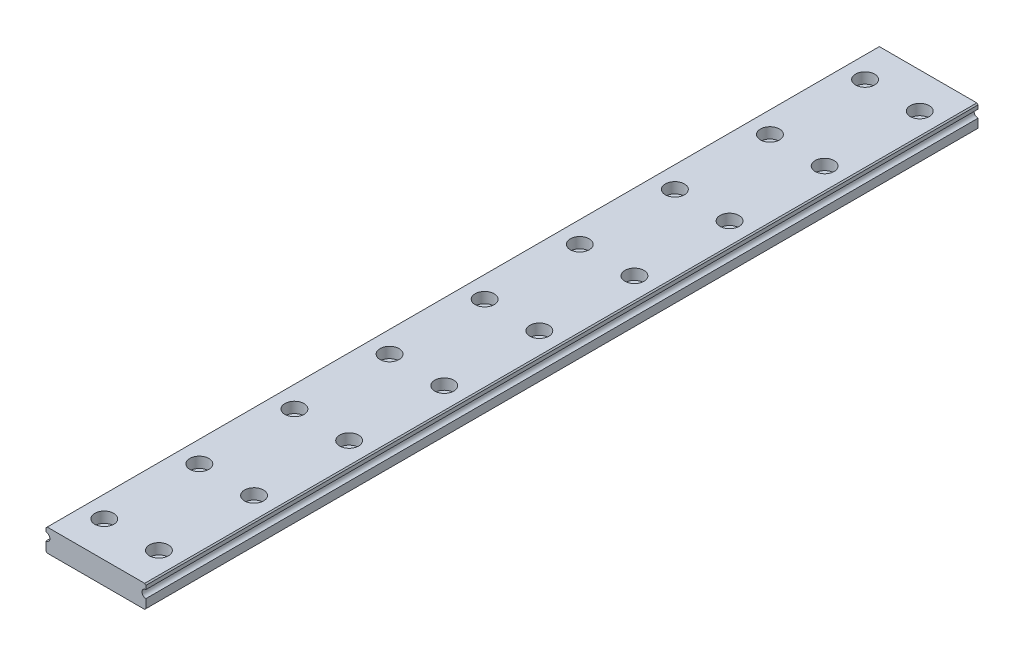
SolidWorks part; units mm, degrees
ref_plane "Front Plane" through (0, 0, 0) normal (0, 0, 1) x (1, 0, 0)
ref_plane "Top Plane" through (0, 0, 0) normal (0, 1, 0) x (1, 0, 0)
ref_plane "Right Plane" through (0, 0, 0) normal (1, 0, 0) x (0, 0, -1)
ref_plane "Plane1" through (0, 0, 0) normal (0, 0, 1) x (1, 0, 0)
sketch "Sketch1" plane through (0, 0, 0) normal (0, 0, 1) x (1, 0, 0)
  line L0 (-21, 9.005) -> (-21, 7.456)
  line L1 (-21, 4.176) -> (-21, 0.495)
  line L2 (-21, 0.495) -> (-20.505, 0)
  line L3 (-20.505, 0) -> (20.505, 0)
  line L4 (20.505, 0) -> (21, 0.495)
  line L5 (21, 0.495) -> (21, 4.176)
  line L6 (21, 7.456) -> (21, 9.005)
  line L7 (21, 9.005) -> (20.505, 9.5)
  line L8 (20.505, 9.5) -> (-20.505, 9.5)
  line L9 (-20.505, 9.5) -> (-21, 9.005)
  arc A0 (-21, 7.456) -> (-21, 4.176) centre (-21, 5.816) cw
  arc A1 (21, 4.176) -> (21, 7.456) centre (21, 5.816) cw
extrude "Boss-Extrude1" add sketch "Sketch1" along normal blind 350
ref_plane "Plane2" through (11.5, 0, 0) normal (1, 0, 0) x (0, 0, -1)
sketch "Sketch2" plane through (11.5, 0, 0) normal (1, 0, 0) x (0, 0, -1)
  line L0 (-15, 9.5) -> (-11, 9.5)
  line L1 (-11, 9.5) -> (-11, 5)
  line L2 (-11, 5) -> (-12.75, 5)
  line L3 (-12.75, 5) -> (-12.75, 0)
  line L4 (-12.75, 0) -> (-15, 0)
  line L5 (-15, 0) -> (-15, 9.5)
  line L6 (-15, 0) -> (-15, 9.5) construction
revolve "Cut-Revolve1" cut sketch "Sketch2" angle 360 about L6
ref_plane "Plane3" through (11.5, 0, 0) normal (1, 0, 0) x (0, 0, -1)
sketch "Sketch3" plane through (11.5, 0, 0) normal (1, 0, 0) x (0, 0, -1)
  line L0 (-335, 9.5) -> (-331, 9.5)
  line L1 (-331, 9.5) -> (-331, 5)
  line L2 (-331, 5) -> (-332.75, 5)
  line L3 (-332.75, 5) -> (-332.75, 0)
  line L4 (-332.75, 0) -> (-335, 0)
  line L5 (-335, 0) -> (-335, 9.5)
  line L6 (-335, 0) -> (-335, 9.5) construction
revolve "Cut-Revolve2" cut sketch "Sketch3" angle 360 about L6
ref_plane "Plane4" through (-11.5, 0, 0) normal (1, 0, 0) x (0, 0, -1)
sketch "Sketch4" plane through (-11.5, 0, 0) normal (1, 0, 0) x (0, 0, -1)
  line L0 (-335, 9.5) -> (-331, 9.5)
  line L1 (-331, 9.5) -> (-331, 5)
  line L2 (-331, 5) -> (-332.75, 5)
  line L3 (-332.75, 5) -> (-332.75, 0)
  line L4 (-332.75, 0) -> (-335, 0)
  line L5 (-335, 0) -> (-335, 9.5)
  line L6 (-335, 0) -> (-335, 9.5) construction
revolve "Cut-Revolve3" cut sketch "Sketch4" angle 360 about L6
ref_plane "Plane5" through (11.5, 0, 0) normal (1, 0, 0) x (0, 0, -1)
sketch "Sketch5" plane through (11.5, 0, 0) normal (1, 0, 0) x (0, 0, -1)
  line L0 (-295, 9.5) -> (-291, 9.5)
  line L1 (-291, 9.5) -> (-291, 5)
  line L2 (-291, 5) -> (-292.75, 5)
  line L3 (-292.75, 5) -> (-292.75, 0)
  line L4 (-292.75, 0) -> (-295, 0)
  line L5 (-295, 0) -> (-295, 9.5)
  line L6 (-295, 0) -> (-295, 9.5) construction
revolve "Cut-Revolve4" cut sketch "Sketch5" angle 360 about L6
ref_plane "Plane6" through (-11.5, 0, 0) normal (1, 0, 0) x (0, 0, -1)
sketch "Sketch6" plane through (-11.5, 0, 0) normal (1, 0, 0) x (0, 0, -1)
  line L0 (-295, 9.5) -> (-291, 9.5)
  line L1 (-291, 9.5) -> (-291, 5)
  line L2 (-291, 5) -> (-292.75, 5)
  line L3 (-292.75, 5) -> (-292.75, 0)
  line L4 (-292.75, 0) -> (-295, 0)
  line L5 (-295, 0) -> (-295, 9.5)
  line L6 (-295, 0) -> (-295, 9.5) construction
revolve "Cut-Revolve5" cut sketch "Sketch6" angle 360 about L6
ref_plane "Plane7" through (11.5, 0, 0) normal (1, 0, 0) x (0, 0, -1)
sketch "Sketch7" plane through (11.5, 0, 0) normal (1, 0, 0) x (0, 0, -1)
  line L0 (-255, 9.5) -> (-251, 9.5)
  line L1 (-251, 9.5) -> (-251, 5)
  line L2 (-251, 5) -> (-252.75, 5)
  line L3 (-252.75, 5) -> (-252.75, 0)
  line L4 (-252.75, 0) -> (-255, 0)
  line L5 (-255, 0) -> (-255, 9.5)
  line L6 (-255, 0) -> (-255, 9.5) construction
revolve "Cut-Revolve6" cut sketch "Sketch7" angle 360 about L6
ref_plane "Plane8" through (-11.5, 0, 0) normal (1, 0, 0) x (0, 0, -1)
sketch "Sketch8" plane through (-11.5, 0, 0) normal (1, 0, 0) x (0, 0, -1)
  line L0 (-255, 9.5) -> (-251, 9.5)
  line L1 (-251, 9.5) -> (-251, 5)
  line L2 (-251, 5) -> (-252.75, 5)
  line L3 (-252.75, 5) -> (-252.75, 0)
  line L4 (-252.75, 0) -> (-255, 0)
  line L5 (-255, 0) -> (-255, 9.5)
  line L6 (-255, 0) -> (-255, 9.5) construction
revolve "Cut-Revolve7" cut sketch "Sketch8" angle 360 about L6
ref_plane "Plane9" through (11.5, 0, 0) normal (1, 0, 0) x (0, 0, -1)
sketch "Sketch9" plane through (11.5, 0, 0) normal (1, 0, 0) x (0, 0, -1)
  line L0 (-215, 9.5) -> (-211, 9.5)
  line L1 (-211, 9.5) -> (-211, 5)
  line L2 (-211, 5) -> (-212.75, 5)
  line L3 (-212.75, 5) -> (-212.75, 0)
  line L4 (-212.75, 0) -> (-215, 0)
  line L5 (-215, 0) -> (-215, 9.5)
  line L6 (-215, 0) -> (-215, 9.5) construction
revolve "Cut-Revolve8" cut sketch "Sketch9" angle 360 about L6
ref_plane "Plane10" through (-11.5, 0, 0) normal (1, 0, 0) x (0, 0, -1)
sketch "Sketch10" plane through (-11.5, 0, 0) normal (1, 0, 0) x (0, 0, -1)
  line L0 (-215, 9.5) -> (-211, 9.5)
  line L1 (-211, 9.5) -> (-211, 5)
  line L2 (-211, 5) -> (-212.75, 5)
  line L3 (-212.75, 5) -> (-212.75, 0)
  line L4 (-212.75, 0) -> (-215, 0)
  line L5 (-215, 0) -> (-215, 9.5)
  line L6 (-215, 0) -> (-215, 9.5) construction
revolve "Cut-Revolve9" cut sketch "Sketch10" angle 360 about L6
ref_plane "Plane11" through (11.5, 0, 0) normal (1, 0, 0) x (0, 0, -1)
sketch "Sketch11" plane through (11.5, 0, 0) normal (1, 0, 0) x (0, 0, -1)
  line L0 (-175, 9.5) -> (-171, 9.5)
  line L1 (-171, 9.5) -> (-171, 5)
  line L2 (-171, 5) -> (-172.75, 5)
  line L3 (-172.75, 5) -> (-172.75, 0)
  line L4 (-172.75, 0) -> (-175, 0)
  line L5 (-175, 0) -> (-175, 9.5)
  line L6 (-175, 0) -> (-175, 9.5) construction
revolve "Cut-Revolve10" cut sketch "Sketch11" angle 360 about L6
ref_plane "Plane12" through (-11.5, 0, 0) normal (1, 0, 0) x (0, 0, -1)
sketch "Sketch12" plane through (-11.5, 0, 0) normal (1, 0, 0) x (0, 0, -1)
  line L0 (-175, 9.5) -> (-171, 9.5)
  line L1 (-171, 9.5) -> (-171, 5)
  line L2 (-171, 5) -> (-172.75, 5)
  line L3 (-172.75, 5) -> (-172.75, 0)
  line L4 (-172.75, 0) -> (-175, 0)
  line L5 (-175, 0) -> (-175, 9.5)
  line L6 (-175, 0) -> (-175, 9.5) construction
revolve "Cut-Revolve11" cut sketch "Sketch12" angle 360 about L6
ref_plane "Plane13" through (11.5, 0, 0) normal (1, 0, 0) x (0, 0, -1)
sketch "Sketch13" plane through (11.5, 0, 0) normal (1, 0, 0) x (0, 0, -1)
  line L0 (-135, 9.5) -> (-131, 9.5)
  line L1 (-131, 9.5) -> (-131, 5)
  line L2 (-131, 5) -> (-132.75, 5)
  line L3 (-132.75, 5) -> (-132.75, 0)
  line L4 (-132.75, 0) -> (-135, 0)
  line L5 (-135, 0) -> (-135, 9.5)
  line L6 (-135, 0) -> (-135, 9.5) construction
revolve "Cut-Revolve12" cut sketch "Sketch13" angle 360 about L6
ref_plane "Plane14" through (-11.5, 0, 0) normal (1, 0, 0) x (0, 0, -1)
sketch "Sketch14" plane through (-11.5, 0, 0) normal (1, 0, 0) x (0, 0, -1)
  line L0 (-135, 9.5) -> (-131, 9.5)
  line L1 (-131, 9.5) -> (-131, 5)
  line L2 (-131, 5) -> (-132.75, 5)
  line L3 (-132.75, 5) -> (-132.75, 0)
  line L4 (-132.75, 0) -> (-135, 0)
  line L5 (-135, 0) -> (-135, 9.5)
  line L6 (-135, 0) -> (-135, 9.5) construction
revolve "Cut-Revolve13" cut sketch "Sketch14" angle 360 about L6
ref_plane "Plane15" through (11.5, 0, 0) normal (1, 0, 0) x (0, 0, -1)
sketch "Sketch15" plane through (11.5, 0, 0) normal (1, 0, 0) x (0, 0, -1)
  line L0 (-95, 9.5) -> (-91, 9.5)
  line L1 (-91, 9.5) -> (-91, 5)
  line L2 (-91, 5) -> (-92.75, 5)
  line L3 (-92.75, 5) -> (-92.75, 0)
  line L4 (-92.75, 0) -> (-95, 0)
  line L5 (-95, 0) -> (-95, 9.5)
  line L6 (-95, 0) -> (-95, 9.5) construction
revolve "Cut-Revolve14" cut sketch "Sketch15" angle 360 about L6
ref_plane "Plane16" through (-11.5, 0, 0) normal (1, 0, 0) x (0, 0, -1)
sketch "Sketch16" plane through (-11.5, 0, 0) normal (1, 0, 0) x (0, 0, -1)
  line L0 (-95, 9.5) -> (-91, 9.5)
  line L1 (-91, 9.5) -> (-91, 5)
  line L2 (-91, 5) -> (-92.75, 5)
  line L3 (-92.75, 5) -> (-92.75, 0)
  line L4 (-92.75, 0) -> (-95, 0)
  line L5 (-95, 0) -> (-95, 9.5)
  line L6 (-95, 0) -> (-95, 9.5) construction
revolve "Cut-Revolve15" cut sketch "Sketch16" angle 360 about L6
ref_plane "Plane17" through (11.5, 0, 0) normal (1, 0, 0) x (0, 0, -1)
sketch "Sketch17" plane through (11.5, 0, 0) normal (1, 0, 0) x (0, 0, -1)
  line L0 (-55, 9.5) -> (-51, 9.5)
  line L1 (-51, 9.5) -> (-51, 5)
  line L2 (-51, 5) -> (-52.75, 5)
  line L3 (-52.75, 5) -> (-52.75, 0)
  line L4 (-52.75, 0) -> (-55, 0)
  line L5 (-55, 0) -> (-55, 9.5)
  line L6 (-55, 0) -> (-55, 9.5) construction
revolve "Cut-Revolve16" cut sketch "Sketch17" angle 360 about L6
ref_plane "Plane18" through (-11.5, 0, 0) normal (1, 0, 0) x (0, 0, -1)
sketch "Sketch18" plane through (-11.5, 0, 0) normal (1, 0, 0) x (0, 0, -1)
  line L0 (-55, 9.5) -> (-51, 9.5)
  line L1 (-51, 9.5) -> (-51, 5)
  line L2 (-51, 5) -> (-52.75, 5)
  line L3 (-52.75, 5) -> (-52.75, 0)
  line L4 (-52.75, 0) -> (-55, 0)
  line L5 (-55, 0) -> (-55, 9.5)
  line L6 (-55, 0) -> (-55, 9.5) construction
revolve "Cut-Revolve17" cut sketch "Sketch18" angle 360 about L6
ref_plane "Plane19" through (-11.5, 0, 0) normal (1, 0, 0) x (0, 0, -1)
sketch "Sketch19" plane through (-11.5, 0, 0) normal (1, 0, 0) x (0, 0, -1)
  line L0 (-15, 9.5) -> (-11, 9.5)
  line L1 (-11, 9.5) -> (-11, 5)
  line L2 (-11, 5) -> (-12.75, 5)
  line L3 (-12.75, 5) -> (-12.75, 0)
  line L4 (-12.75, 0) -> (-15, 0)
  line L5 (-15, 0) -> (-15, 9.5)
  line L6 (-15, 0) -> (-15, 9.5) construction
revolve "Cut-Revolve18" cut sketch "Sketch19" angle 360 about L6
